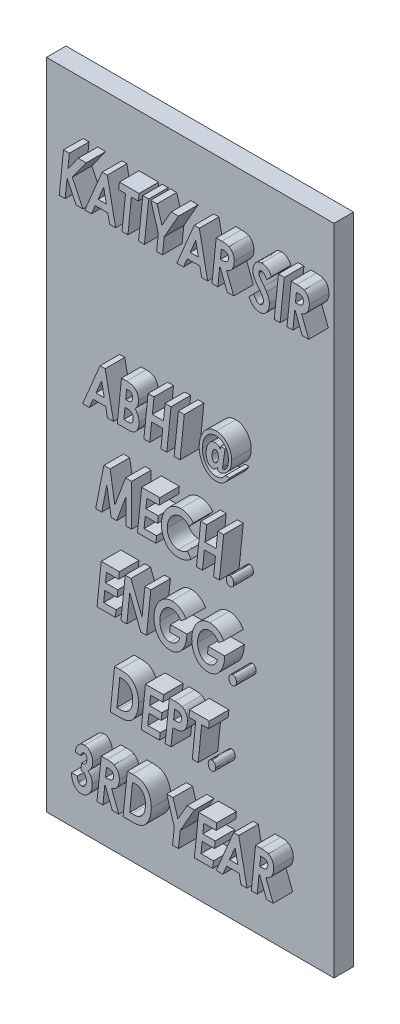
SolidWorks part; units mm, degrees
ref_plane "Front Plane" through (0, 0, 0) normal (0, 0, 1) x (1, 0, 0)
ref_plane "Top Plane" through (0, 0, 0) normal (0, 1, 0) x (1, 0, 0)
ref_plane "Right Plane" through (0, 0, 0) normal (1, 0, 0) x (0, 0, -1)
sketch "Sketch4" plane through (0, 0, 0) normal (0, 0, 1) x (1, 0, 0)
  line L1 (-11, -25) -> (11, -25)
  line L2 (-11, -25) -> (-11, 25)
  line L3 (-11, 25) -> (11, 25)
  line L4 (11, -25) -> (11, 25)
  line L5 (-11, -25) -> (11, 25) construction
  line L6 (-11, 25) -> (11, -25) construction
  point P0 (0, 0)
  dimension "D1" = 50
  dimension "D2" = 22
extrude "Boss-Extrude5" add sketch "Sketch4" along normal blind 1.5
sketch "Sketch6" plane through (0, 0, 1.5) normal (0, 0, 1) x (1, 0, 0)
  text T0 "KATIYAR SIR\r\n\r\n  ABHI @\r\n   MECH.\r\n   ENGG.\r\n    DEPT.\r\n 3RD YEAR" font "Century Gothic" height in points 12
extrude "Boss-Extrude6" add sketch "Sketch6" along normal blind 1.5
